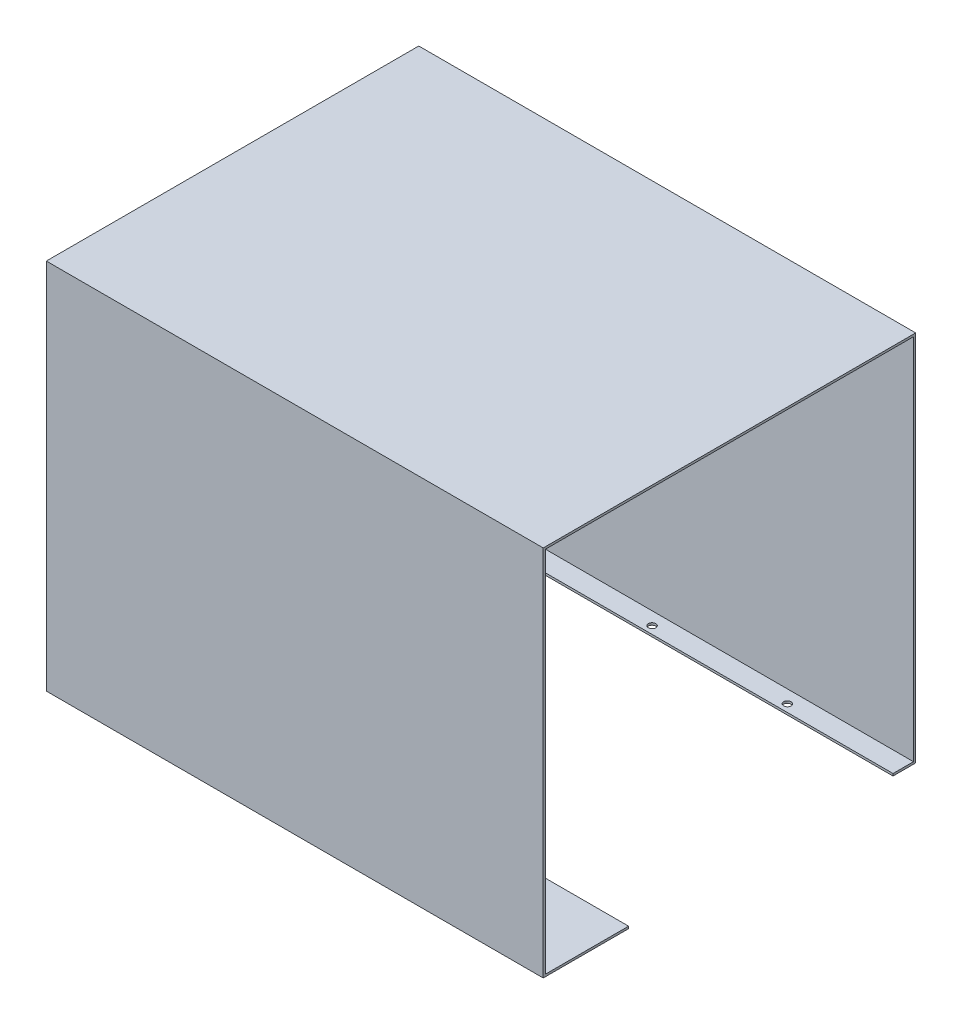
SolidWorks part; units mm, degrees
ref_plane "Alzado" through (0, 0, 0) normal (0, 0, 1) x (1, 0, 0)
ref_plane "Planta" through (0, 0, 0) normal (0, 1, 0) x (1, 0, 0)
ref_plane "Vista lateral" through (0, 0, 0) normal (1, 0, 0) x (0, 0, -1)
sketch "Croquis1" plane through (0, 0, 0) normal (0, 0, 1) x (1, 0, 0)
  line L1 (0, 0) -> (428, 0)
  line L2 (0, 0) -> (0, 317)
  line L3 (0, 317) -> (428, 317)
  line L4 (428, 0) -> (428, 317)
  dimension "D1" = 317
  dimension "D2" = 428
extrude "Saliente-Extruir1" add sketch "Croquis1" along normal blind 1.9
sketch "Croquis3" plane through (0, 0, 1.9) normal (0, 0, 1) x (1, 0, 0)
  line L1 (428, 317) -> (0, 317)
  line L2 (428, 317) -> (428, 318.9)
  line L3 (428, 318.9) -> (0, 318.9)
  line L4 (0, 317) -> (0, 318.9)
  dimension "D1" = 1.9
extrude "Saliente-Extruir2" add sketch "Croquis3" against normal blind 320.8
sketch "Croquis4" plane through (0, 317, 0) normal (0, -1, 0) x (1, 0, 0)
  line L0 (0, -318.9) -> (0, 0) construction
  line L1 (428, -318.9) -> (0, -318.9)
  line L2 (428, -318.9) -> (428, -317)
  line L3 (428, -317) -> (0, -317)
  line L4 (0, -318.9) -> (0, -317)
  dimension "D1" = 1.9
extrude "Saliente-Extruir3" add sketch "Croquis4" along normal up to surface (317 mm away) up to face at (214, 0, 0.95)
sketch "Croquis6" plane through (0, 0, -318.9) normal (0, 0, -1) x (-1, 0, 0)
  line L1 (-428, 0) -> (0, 0)
  line L2 (-428, 0) -> (-428, -1.9)
  line L3 (-428, -1.9) -> (0, -1.9)
  line L4 (0, 0) -> (0, -1.9)
  dimension "D1" = 1.9
extrude "Saliente-Extruir4" add sketch "Croquis6" against normal blind 19.52
sketch "Croquis7" plane through (0, 0, 1.9) normal (0, 0, 1) x (1, 0, 0)
  line L1 (0, 0) -> (428, 0)
  line L2 (0, 0) -> (0, -1.9)
  line L3 (0, -1.9) -> (428, -1.9)
  line L4 (428, 0) -> (428, -1.9)
extrude "Saliente-Extruir5" add sketch "Croquis7" against normal blind 73.52
sketch "Croquis8" plane through (0, -1.9, 0) normal (0, -1, 0) x (1, 0, 0)
  line L0 (214, -318.9) -> (214, -299.38) construction
  line L2 (428, -318.9) -> (0, -318.9) construction
  line L3 (0, -299.38) -> (0, -318.9) construction
  line L6 (428, -185.5) -> (0, -185.5) construction
  line L10 (428, -299.38) -> (0, -299.38) construction
  line L11 (428, -299.38) -> (428, -318.9) construction
  line L12 (428, -299.38) -> (428, -71.62) construction
  line L13 (0, -317) -> (0, 0) construction
  line L14 (214, -52.1) -> (214, -71.62) construction
  circle A0 centre (214, -305.88) radius 3.175
  circle A1 centre (330.5, -305.88) radius 3.175
  circle A2 centre (97.5, -305.88) radius 3.175
  circle A3 centre (97.5, -65.12) radius 3.175
  circle A4 centre (330.5, -65.12) radius 3.175
  circle A5 centre (214, -65.12) radius 3.175
  point P24 (428, -309.14)
  dimension "D1" = 13.02
  dimension "D2" = 13.02
  dimension "D4" = 13.02
  dimension "D5" = 6.35
  dimension "D3" = 6.35
  dimension "D6" = 97.5
  dimension "D7" = 6.35
  dimension "D8" = 97.5
extrude "Cortar-Extruir1" cut sketch "Croquis8" against normal up to surface (1.9 mm away) up to face at (214, 0, -308.19)
equation "\"1.9i\"=54.8243"
